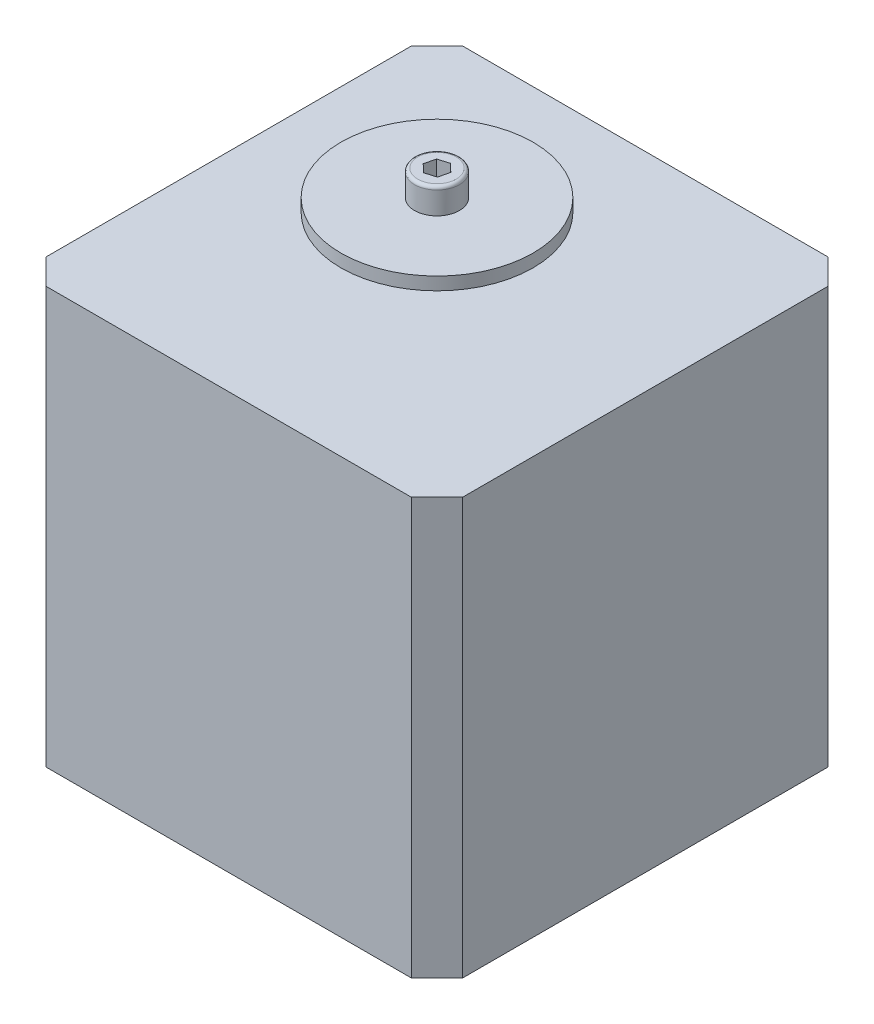
SolidWorks part; units mm, degrees
ref_plane "Front" through (0, 0, 0) normal (0, 0, 1) x (1, 0, 0)
ref_plane "Top" through (0, 0, 0) normal (0, 1, 0) x (1, 0, 0)
ref_plane "Right" through (0, 0, 0) normal (1, 0, 0) x (0, 0, -1)
sketch "Esquisse3" plane through (0, 0, 0) normal (0, 1, 0) x (1, 0, 0)
  line L1 (-32.5, -32.5) -> (32.5, -32.5)
  line L2 (-32.5, -32.5) -> (-32.5, 32.5)
  line L3 (-32.5, 32.5) -> (32.5, 32.5)
  line L4 (32.5, -32.5) -> (32.5, 32.5)
  line L5 (0, 32.5) -> (0, -32.5) construction
  line L6 (-32.5, 0) -> (32.5, 0) construction
  line L7 (-30, -30) -> (30, -30) construction
  line L8 (-30, -30) -> (-30, 30) construction
  line L9 (-30, 30) -> (30, 30) construction
  line L10 (30, -30) -> (30, 30) construction
  line L11 (0, 30) -> (0, -30) construction
  line L12 (-30, 0) -> (30, 0) construction
  point P0 (0, 0)
  point P4 (0, 0)
  dimension "D1" = 65
  dimension "D2" = 60
extrude "Boss.-Extru.3" add sketch "Esquisse3" along normal blind 65 separate body
chamfer "Chanfrein1" distance 4 angle 45 4 edges at (32.5, 32.5, 32.5) (-32.5, 32.5, 32.5) (32.5, 32.5, -32.5) (-32.5, 32.5, -32.5)
sketch "Esquisse4" plane through (0, 0, 0) normal (0, 0, 1) x (1, 0, 0)
  line L0 (0, 65) -> (0, 79)
  line L2 (3.5, 75) -> (15, 75)
  line L3 (15, 75) -> (15, 73)
  line L4 (15, 73) -> (3, 73)
  line L5 (3, 73) -> (3, 65)
  line L6 (3, 65) -> (0, 65)
  line L7 (0, 79) -> (0, 82.5) construction
  line L8 (-28.5, 65) -> (28.5, 65) construction
  line L9 (3.5, 75) -> (3.5, 79)
  line L10 (3.5, 79) -> (0, 79)
  point P12 (0, 78.3688)
  dimension "D1" = 6
  dimension "D2" = 2
  dimension "D3" = 8
  dimension "D4" = 30
  dimension "D5" = 7
  dimension "D6" = 4
revolve "Révolution1" add sketch "Esquisse4" angle 360 about L7
sketch "Esquisse5" plane through (0, 79, 0) normal (0, 1, 0) x (1, 0, 0)
  line L1 (1.262, -1.1863) -> (1.6584, 0.4998)
  line L2 (1.6584, 0.4998) -> (0.3964, 1.6861)
  line L3 (0.3964, 1.6861) -> (-1.262, 1.1863)
  line L4 (-1.262, 1.1863) -> (-1.6584, -0.4998)
  line L5 (-1.6584, -0.4998) -> (-0.3964, -1.6861)
  line L6 (-0.3964, -1.6861) -> (1.262, -1.1863)
  circle A0 centre (0, 0) radius 1.5 construction
  dimension "D1" = 3
extrude "Enlèv. mat.-Extru.1" cut sketch "Esquisse5" against normal blind 2.5
fillet "Congé1" radius 0.5 1 edges at (0, 79, -3.5)
